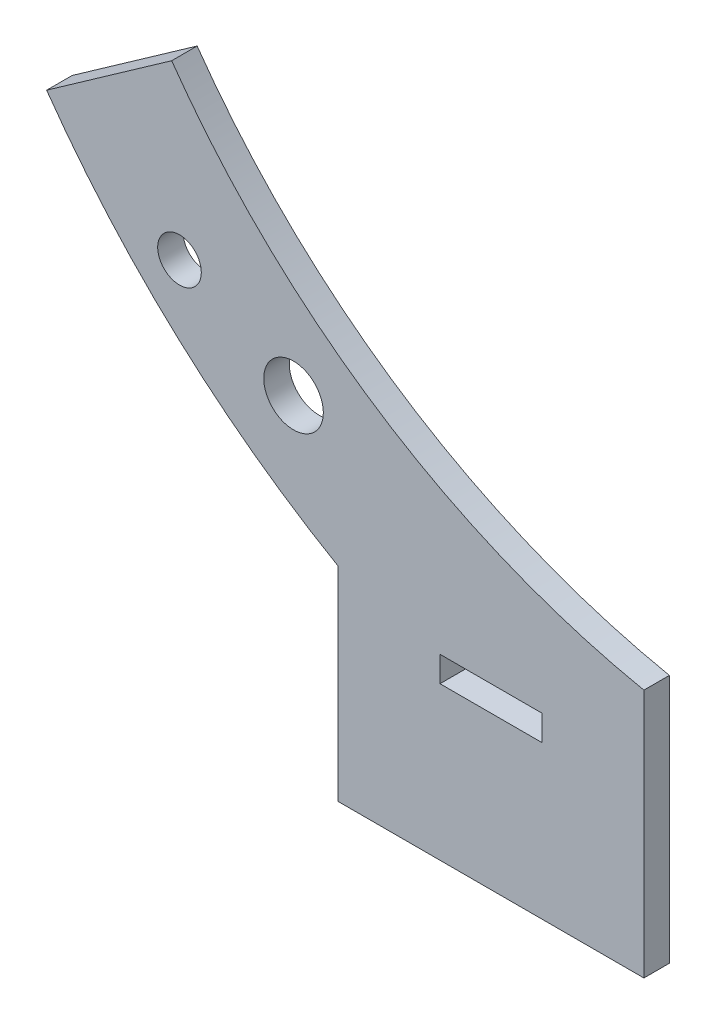
SolidWorks part; units mm, degrees
ref_plane "Front Plane" through (0, 0, 0) normal (0, 0, 1) x (1, 0, 0)
ref_plane "Top Plane" through (0, 0, 0) normal (0, 1, 0) x (1, 0, 0)
ref_plane "Right Plane" through (0, 0, 0) normal (1, 0, 0) x (0, 0, -1)
sketch "Sketch1" plane through (0, 0, 0) normal (0, 0, 1) x (1, 0, 0)
  line L2 (-19.05, -124.3867) -> (-19.05, -93.3256)
  line L3 (-57.15, -98.9867) -> (-57.15, -124.3867)
  line L8 (-93.458, -65.8034) -> (-77.8817, -54.8362)
  line L9 (-77.8817, -54.8362) -> (0, 0) construction
  line L10 (0, 0) -> (0, -124.3867) construction
  line L12 (0, -124.3867) -> (-19.05, -124.3867) construction
  line L13 (-57.15, -124.3867) -> (-19.05, -124.3867)
  line L15 (-44.45, -105.3367) -> (-31.75, -105.3367)
  line L16 (-44.45, -105.3367) -> (-44.45, -102.1617)
  line L17 (-44.45, -102.1617) -> (-31.75, -102.1617)
  line L18 (-31.75, -105.3367) -> (-31.75, -102.1617)
  arc A1 (-19.05, -93.3256) -> (-77.8817, -54.8362) centre (0, 0) cw
  arc A2 (-57.15, -98.9867) -> (-93.458, -65.8034) centre (0, 0) cw
  circle A3 centre (-76.9042, -75.8372) radius 2.7155
  circle A4 centre (-62.697, -83.3649) radius 3.7108
  dimension "D1" = 12.7
  dimension "D2" = 3.175
  dimension "D3" = 114.3
  dimension "D4" = 12.7
  dimension "D5" = 95.25
  dimension "D6" = 25.4
  dimension "D7" = 19.05
  dimension "D8" = 19.05
  dimension "D9" = 38.1
extrude "Boss-Extrude1" add sketch "Sketch1" along normal blind 3.175
